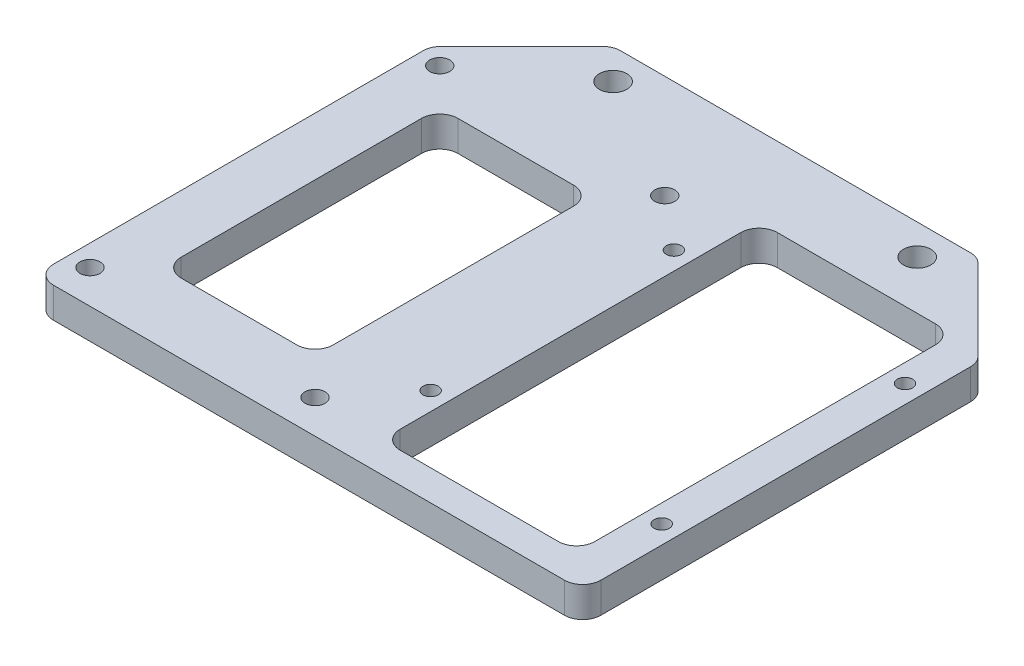
SolidWorks part; units mm, degrees
ref_plane "Front Plane" through (0, 0, 0) normal (0, 0, 1) x (1, 0, 0)
ref_plane "Top Plane" through (0, 0, 0) normal (0, 1, 0) x (1, 0, 0)
ref_plane "Right Plane" through (0, 0, 0) normal (1, 0, 0) x (0, 0, -1)
sketch "Sketch1" plane through (0, 0, 0) normal (0, 1, 0) x (1, 0, 0)
  line L0 (0, 0) -> (0, 40) construction
  line L1 (-45, 40) -> (45, 40)
  line L2 (-45, 40) -> (-45, -40)
  line L3 (-45, -40) -> (45, -40)
  line L4 (45, 40) -> (45, -40)
  line L5 (-45, 40) -> (45, -40) construction
  line L6 (-45, -40) -> (45, 40) construction
  line L7 (23, -4) -> (23, 27) construction
  line L16 (-41.5, -34.5) -> (-4.5, -34.5) construction
  line L17 (-41.5, -34.5) -> (-41.5, 23) construction
  line L18 (-41.5, 23) -> (-4.5, 23) construction
  line L19 (-4.5, -34.5) -> (-4.5, 23) construction
  line L20 (-41.5, -34.5) -> (-4.5, 23) construction
  line L21 (-41.5, 23) -> (-4.5, -34.5) construction
  line L22 (39, -35) -> (7, -35)
  line L23 (39, -35) -> (39, 27)
  line L24 (39, 27) -> (7, 27)
  line L25 (7, -35) -> (7, 27)
  line L26 (39, -35) -> (7, 27) construction
  line L27 (39, 27) -> (7, -35) construction
  line L28 (-10.5, -28.5) -> (-35.5, -28.5)
  line L29 (-10.5, -28.5) -> (-10.5, 17)
  line L30 (-10.5, 17) -> (-35.5, 17)
  line L31 (-35.5, -28.5) -> (-35.5, 17)
  line L32 (-10.5, -28.5) -> (-35.5, 17) construction
  line L33 (-10.5, 17) -> (-35.5, -28.5) construction
  line L35 (4, 16) -> (42, 16) construction
  line L36 (4, 16) -> (4, -24) construction
  line L37 (4, -24) -> (42, -24) construction
  line L38 (42, 16) -> (42, -24) construction
  line L39 (4, 16) -> (42, -24) construction
  line L40 (4, -24) -> (42, 16) construction
  circle A0 centre (-25, 35) radius 2.25
  circle A1 centre (25, 35) radius 2.25
  circle A10 centre (-41.5, 23) radius 1.65
  circle A11 centre (-4.5, 23) radius 1.65
  circle A12 centre (-4.5, -34.5) radius 1.65
  circle A13 centre (-41.5, -34.5) radius 1.65
  circle A16 centre (4, 16) radius 1.25
  circle A17 centre (42, 16) radius 1.25
  circle A18 centre (42, -24) radius 1.25
  circle A19 centre (4, -24) radius 1.25
  point P0 (0, 0)
  point P12 (-23, -5.75)
  point P20 (-23, -5.75)
  point P22 (23, -4)
  dimension "D1" = 4.5
  dimension "D2" = 50
  dimension "D8" = 57.5
  dimension "D5" = 5
  dimension "D9" = 23
  dimension "D6" = 3.3
  dimension "D18" = 38
  dimension "D17" = 2.5
  dimension "D3" = 90
  dimension "D4" = 80
  dimension "D7" = 37
  dimension "D10" = 12
  dimension "D11" = 32
  dimension "D12" = 62
  dimension "D13" = 8
  dimension "D14" = 23
  dimension "D15" = 6
  dimension "D16" = 6
  dimension "D19" = 40
extrude "Boss-Extrude1" add sketch "Sketch1" along normal blind 5
chamfer "Chamfer1" distance 15 2 edges at (45, 2.5, -40) (-45, 2.5, -40)
fillet "Fillet1" radius 3 14 edges at (39, 2.5, 35) (7, 2.5, 35) (39, 2.5, -27) (7, 2.5, -27) (-10.5, 2.5, 28.5) (-35.5, 2.5, 28.5) (-10.5, 2.5, -17) (-35.5, 2.5, -17) (45, 2.5, -25) (30, 2.5, -40) (45, 2.5, 40) (-45, 2.5, 40) (-45, 2.5, -25) (-30, 2.5, -40)
